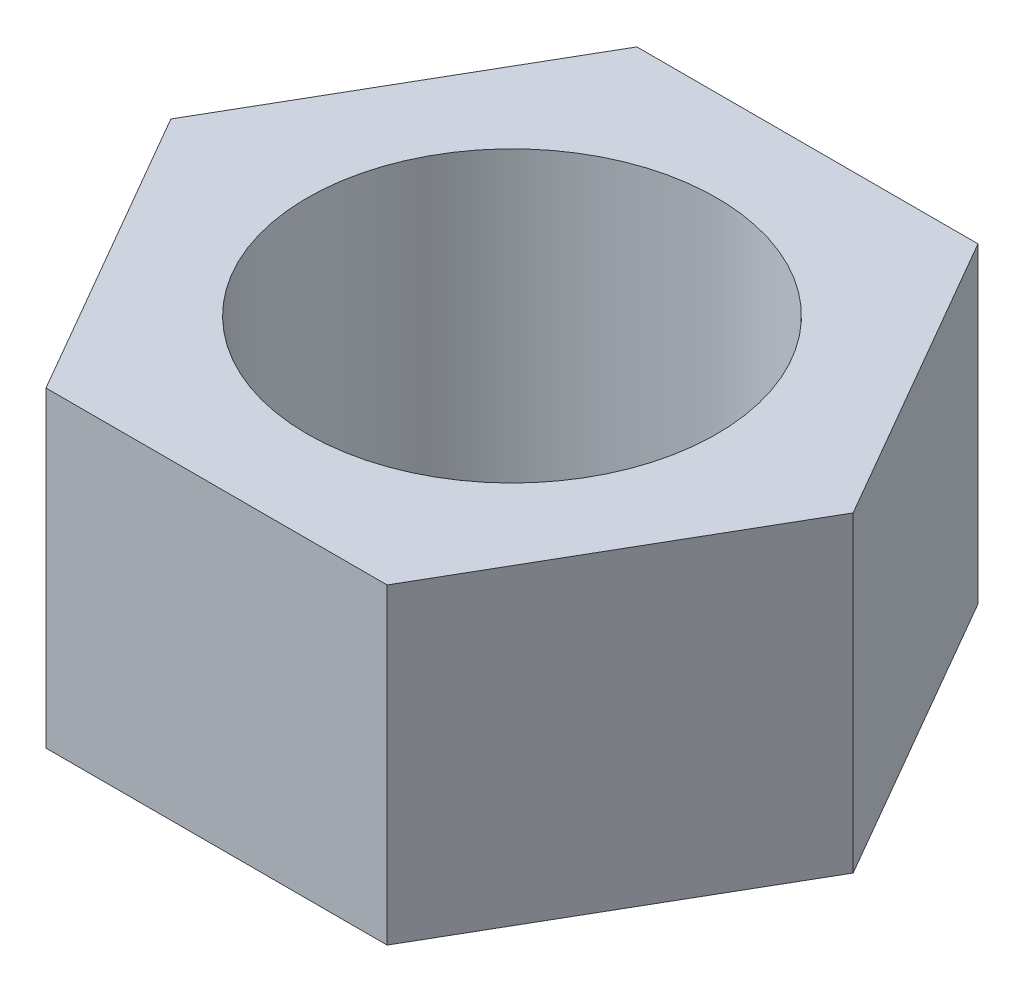
SolidWorks part; units mm, degrees
ref_plane "Front Plane" through (0, 0, 0) normal (0, 0, 1) x (1, 0, 0)
ref_plane "Top Plane" through (0, 0, 0) normal (0, 1, 0) x (1, 0, 0)
ref_plane "Right Plane" through (0, 0, 0) normal (1, 0, 0) x (0, 0, -1)
sketch "Sketch1" plane through (0, 0, 0) normal (0, 1, 0) x (1, 0, 0)
  line L1 (3500, 0) -> (1750, 3031.0889)
  line L2 (1750, 3031.0889) -> (-1750, 3031.0889)
  line L3 (-1750, 3031.0889) -> (-3500, 0)
  line L4 (-3500, 0) -> (-1750, -3031.0889)
  line L5 (-1750, -3031.0889) -> (1750, -3031.0889)
  line L6 (1750, -3031.0889) -> (3500, 0)
  circle A0 centre (0, 0) radius 3031.0889 construction
  circle A1 centre (0, 0) radius 2100
  dimension "D1" = 7000
extrude "Boss-Extrude1" add sketch "Sketch1" along normal blind 3200
